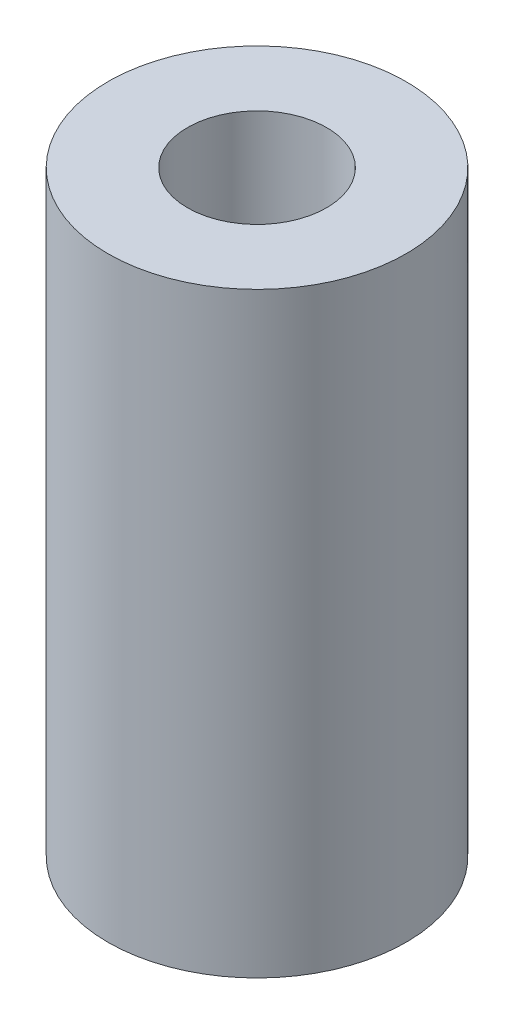
SolidWorks part; units mm, degrees
ref_plane "Front Plane" through (0, 0, 0) normal (0, 0, 1) x (1, 0, 0)
ref_plane "Top Plane" through (0, 0, 0) normal (0, 1, 0) x (1, 0, 0)
ref_plane "Right Plane" through (0, 0, 0) normal (1, 0, 0) x (0, 0, -1)
sketch "Esquisse1" plane through (0, 0, 0) normal (0, 1, 0) x (1, 0, 0)
  circle A0 centre (0, 0) radius 1.4
  circle A1 centre (0, 0) radius 3
extrude "Boss.-Extru.1" add sketch "Esquisse1" along normal blind 12
